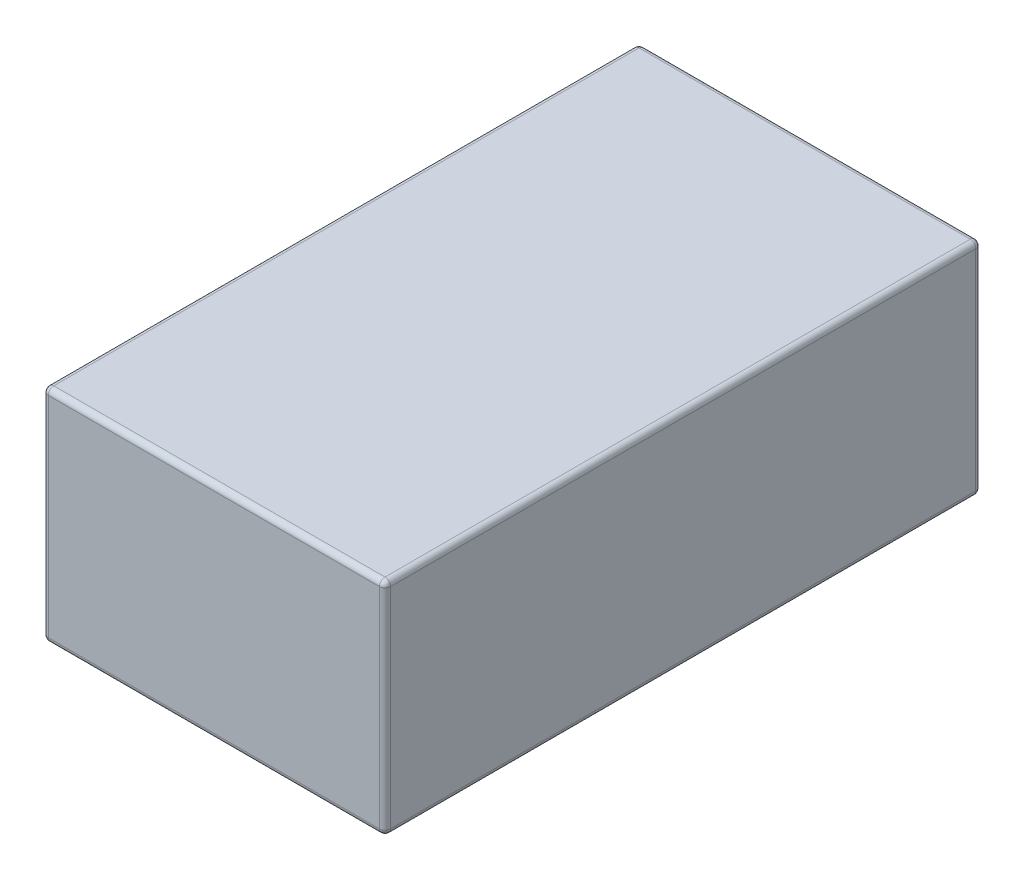
SolidWorks part; units mm, degrees
material "纯金"
ref_plane "前视基准面" through (0, 0, 0) normal (0, 0, 1) x (1, 0, 0)
ref_plane "上视基准面" through (0, 0, 0) normal (0, 1, 0) x (1, 0, 0)
ref_plane "右视基准面" through (0, 0, 0) normal (1, 0, 0) x (0, 0, -1)
sketch "草图1" plane through (0, 0, 0) normal (0, 1, 0) x (1, 0, 0)
  line L1 (-31, -54) -> (31, -54)
  line L2 (-31, -54) -> (-31, 54)
  line L3 (-31, 54) -> (31, 54)
  line L4 (31, -54) -> (31, 54)
  line L5 (-31, -54) -> (31, 54) construction
  line L6 (-31, 54) -> (31, -54) construction
  point P0 (0, 0)
  dimension "D1" = 108
  dimension "D2" = 62
extrude "凸台-拉伸1" add sketch "草图1" along normal blind 40
sketch "草图3" plane through (0, 0, 0) normal (0, -1, 0) x (1, 0, 0)
  text T0 "电池" font "华文行楷" height 3.5
extrude "切除-拉伸1" cut sketch "草图3" against normal blind 10
fillet "圆角1" radius 1 12 edges at (0, 40, 54) (-31, 40, 0) (0, 40, -54) (31, 40, 0) (-31, 20, 54) (31, 20, 54) (0, 0, 54) (31, 20, -54) (31, 0, 0) (0, 0, -54) (-31, 20, -54) (-31, 0, 0)
